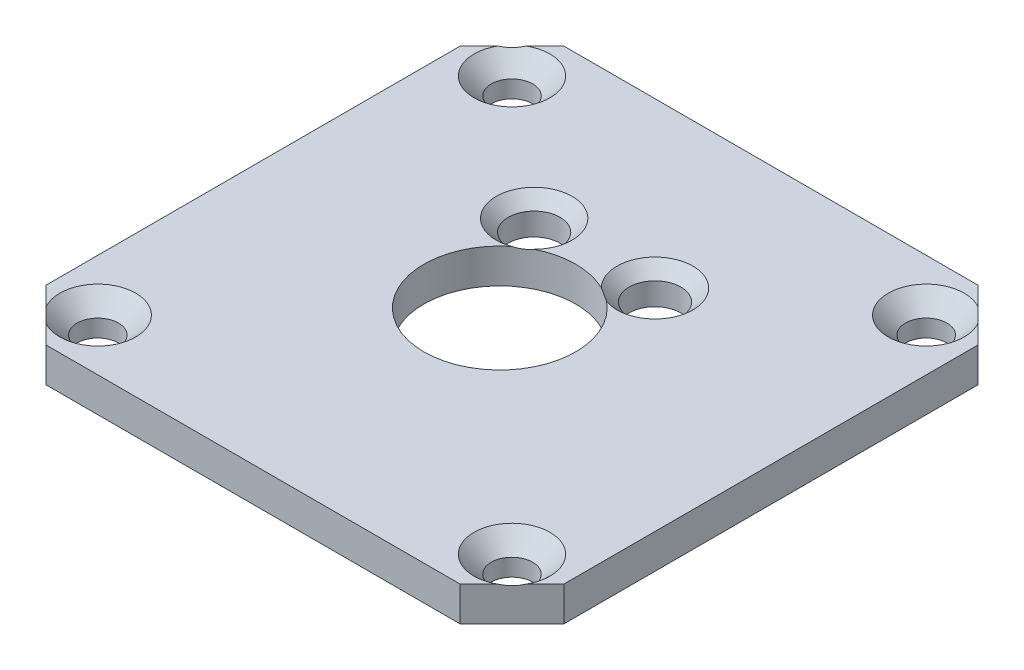
SolidWorks part; units mm, degrees
ref_plane "Front Plane" through (0, 0, 0) normal (0, 0, 1) x (1, 0, 0)
ref_plane "Top Plane" through (0, 0, 0) normal (0, 1, 0) x (1, 0, 0)
ref_plane "Right Plane" through (0, 0, 0) normal (1, 0, 0) x (0, 0, -1)
sketch "Sketch1" plane through (0, 0, 0) normal (0, 1, 0) x (1, 0, 0)
  line L0 (-11.2931, 29.7045) -> (12.7069, 29.7045)
  line L1 (12.7069, 29.7045) -> (15.7069, 26.7045)
  line L2 (15.7069, 26.7045) -> (15.7069, 2.7045)
  line L3 (15.7069, 2.7045) -> (12.7069, -0.2955)
  line L4 (12.7069, -0.2955) -> (-11.2931, -0.2955)
  line L5 (-11.2931, -0.2955) -> (-14.2931, 2.7045)
  line L6 (-14.2931, 26.7045) -> (-14.2931, 2.7045)
  line L7 (-11.2931, 29.7045) -> (-14.2931, 26.7045)
extrude "Boss-Extrude1" add sketch "Sketch1" along normal blind 2
sketch "Sketch2" plane through (0, 2, 0) normal (0, 1, 0) x (1, 0, 0)
  circle A0 centre (0, 14.7045) radius 4.4
  dimension "D1" = 8.8
extrude "Cut-Extrude1" cut sketch "Sketch2" against normal through all
sketch "Sketch5" plane through (0, 2, 0) normal (0, 1, 0) x (1, 0, 0)
  line L0 (-14.2931, 26.7045) -> (-14.2931, 2.7045) construction
  circle A0 centre (-3.5084, 20.2045) radius 1.5
  circle A1 centre (3.4916, 20.2045) radius 1.5
  dimension "D1" = 3
  dimension "D2" = 10.7846
  dimension "D3" = 17.7846
  dimension "D4" = 6.5
extrude "Cut-Extrude2" cut sketch "Sketch5" against normal up to next
hole_wizard "CSK for M2 Flat Head Machine Screw1" positions "3DSketch1" profile "Sketch6" countersink size "M2" standard "ANSI Metric"
sketch3d "3DSketch1"
  line L2 (-3.5084, 0, -20.2045) -> (-3.5084, 2, -20.2045) construction
  line L3 (3.4916, 0, -20.2045) -> (3.4916, 2, -20.2045) construction
  point P19 (-3.5084, 2, -20.2045)
  point P23 (3.4916, 2, -20.2045)
sketch "Sketch6" plane through (-3.5084, 2, -20.2045) normal (1, 0, 0) x (0, 0, 1)
  line L0 (0, 0) -> (0, 43.651)
  line L1 (0, 43.651) -> (1.2, 42.93)
  line L2 (1.2, 42.93) -> (1.2, 1)
  line L3 (1.2, 1) -> (2.2, 0)
  line L5 (2.2, 0) -> (0, 0)
  line L6 (-1.2, 1) -> (-2.2, 0) construction
  line L10 (0, 43.651) -> (-1.2, 42.93) construction
  line L11 (0, -6.35) -> (0, 107.95) construction
  dimension "Hole Dia." = 2.4
  dimension "Hole Depth" = 42.93
  dimension "Near C'Sink Dia." = 4.4
  dimension "Near C'Sink Angle" = 90
  dimension "Drill Angle" = 118
sketch "Sketch7" plane through (0, 2, 0) normal (0, 1, 0) x (1, 0, 0)
  line L0 (-14.2931, 26.7045) -> (-14.2931, 2.7045) construction
  line L1 (12.7069, 29.7045) -> (-11.2931, 29.7045) construction
  line L2 (15.7069, 2.7045) -> (15.7069, 26.7045) construction
  line L3 (-11.2931, -0.2955) -> (12.7069, -0.2955) construction
  circle A0 centre (-11.2931, 26.7045) radius 0.551
  circle A1 centre (-11.2931, 2.7045) radius 0.6431
  circle A2 centre (12.7069, 26.7045) radius 0.6077
  circle A3 centre (12.7069, 2.7045) radius 0.4297
  point P0 (-11.2931, 26.7045)
  point P2 (-11.2931, 2.7045)
  point P4 (12.7069, 26.7045)
  point P6 (12.7069, 2.7045)
  dimension "D9" = 1.102
  dimension "D10" = 1.2155
  dimension "D11" = 0.8595
  dimension "D12" = 1.2861
  dimension "D1" = 3
  dimension "D2" = 3
  dimension "D3" = 3
  dimension "D4" = 3
  dimension "D5" = 3
  dimension "D6" = 3
  dimension "D7" = 3
  dimension "D8" = 3
hole_wizard "CSK for M2 Flat Head Machine Screw2" positions "Sketch7" profile "Sketch8" countersink size "M2" standard "ANSI Metric"
sketch "Sketch8" plane through (-11.2931, 2, -26.7045) normal (1, 0, 0) x (0, 0, 1)
  line L0 (0, 0) -> (0, 43.651)
  line L1 (0, 43.651) -> (1.2, 42.93)
  line L2 (1.2, 42.93) -> (1.2, 1)
  line L3 (1.2, 1) -> (2.2, 0)
  line L5 (2.2, 0) -> (0, 0)
  line L6 (-1.2, 1) -> (-2.2, 0) construction
  line L10 (0, 43.651) -> (-1.2, 42.93) construction
  line L11 (0, -6.35) -> (0, 107.95) construction
  dimension "Hole Dia." = 2.4
  dimension "Hole Depth" = 42.93
  dimension "Near C'Sink Dia." = 4.4
  dimension "Near C'Sink Angle" = 90
  dimension "Drill Angle" = 118
